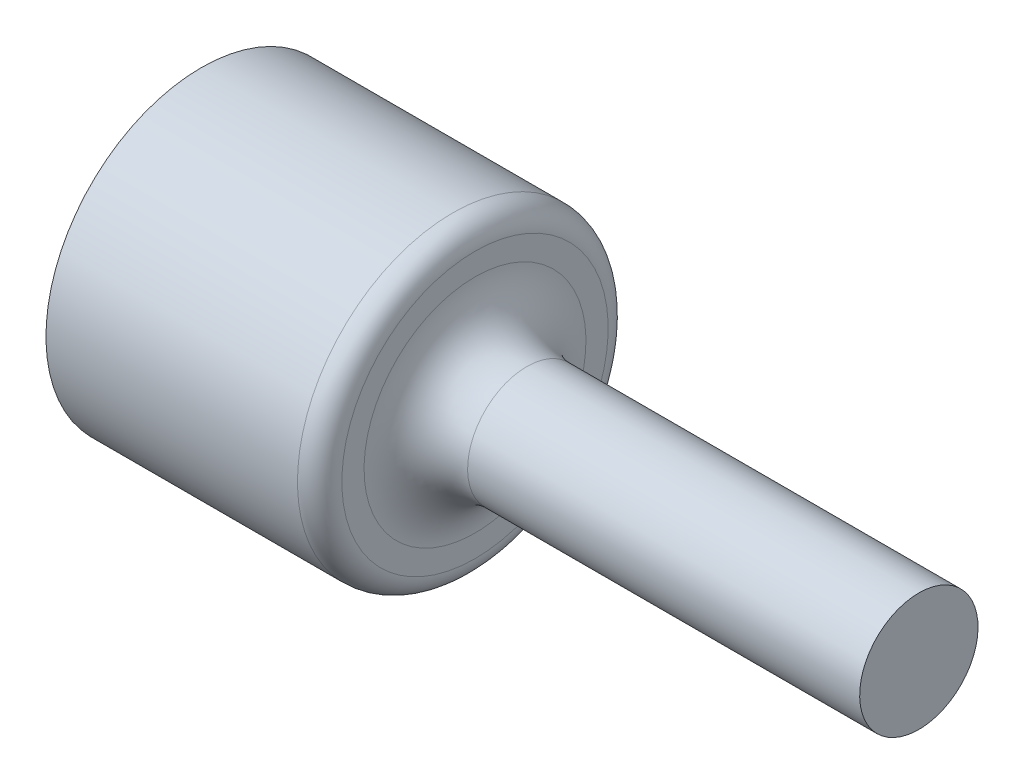
SolidWorks part; units mm, degrees
ref_plane "Front Plane" through (0, 0, 0) normal (0, 0, 1) x (1, 0, 0)
ref_plane "Top Plane" through (0, 0, 0) normal (0, 1, 0) x (1, 0, 0)
ref_plane "Right Plane" through (0, 0, 0) normal (1, 0, 0) x (0, 0, -1)
sketch "Sketch1" plane through (0, 0, 0) normal (0, 0, 1) x (1, 0, 0)
  line L0 (0, 0) -> (0, 21)
  line L1 (0, 21) -> (37, 21)
  line L2 (37, 21) -> (37, 8)
  line L3 (37, 8) -> (97, 8)
  line L4 (97, 8) -> (97, 0)
  line L5 (97, 0) -> (0, 0)
  dimension "D1" = 37
  dimension "D2" = 60
  dimension "D3" = 21
  dimension "D4" = 8
revolve "Revolve1" add sketch "Sketch1" angle 360 about L5
fillet "Fillet1" radius 3 1 edges at (37, 21, 0)
fillet "Fillet2" radius 7 1 edges at (37, 8, 0)
